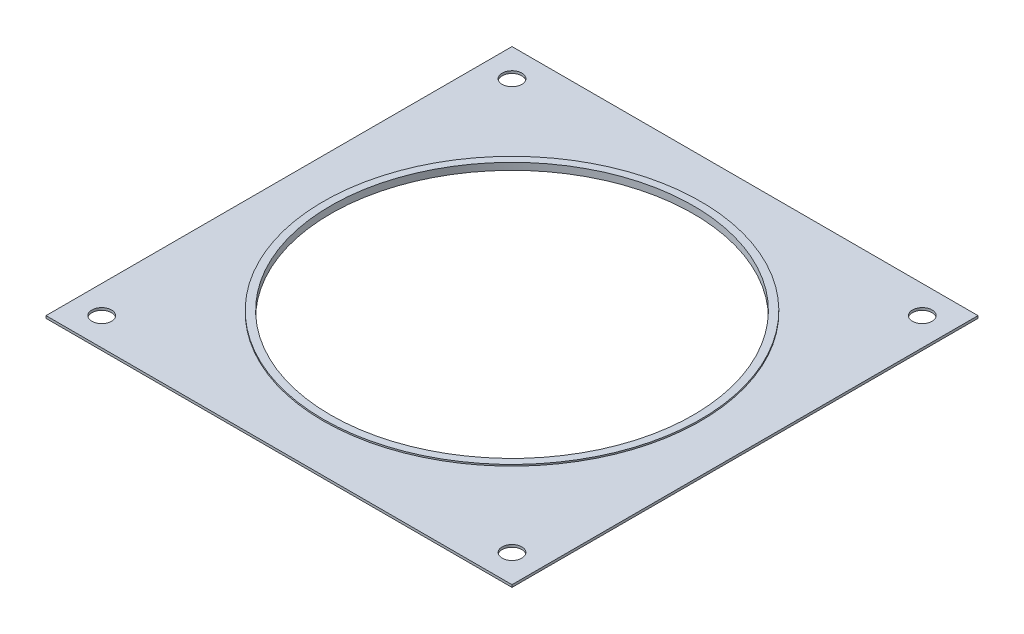
SolidWorks part; units mm, degrees
material "AISI 1020"
ref_plane "Alzado" through (0, 0, 0) normal (0, 0, 1) x (1, 0, 0)
ref_plane "Planta" through (0, 0, 0) normal (0, 1, 0) x (1, 0, 0)
ref_plane "Vista lateral" through (0, 0, 0) normal (1, 0, 0) x (0, 0, -1)
sketch "Croquis1" plane through (0, 0, 0) normal (0, 1, 0) x (1, 0, 0)
  line L1 (-77.1, -77.1) -> (77.1, -77.1)
  line L2 (-77.1, -77.1) -> (-77.1, 77.1)
  line L3 (-77.1, 77.1) -> (77.1, 77.1)
  line L4 (77.1, -77.1) -> (77.1, 77.1)
  line L5 (-77.1, -77.1) -> (77.1, 77.1) construction
  line L6 (-77.1, 77.1) -> (77.1, -77.1) construction
  point P0 (0, 0)
  dimension "D1" = 154.2
  dimension "D2" = 154.2
extrude "Saliente-Extruir1" add sketch "Croquis1" along normal blind 0.8
sketch "Croquis2" plane through (0, 0.8, 0) normal (0, 1, 0) x (1, 0, 0)
  circle A0 centre (0, 0) radius 60
  dimension "D1" = 120
extrude "Cortar-Extruir1" cut sketch "Croquis2" against normal through all
sketch "Croquis3" plane through (0, 0.8, 0) normal (0, 1, 0) x (1, 0, 0)
  circle A0 centre (0, 0) radius 60
  circle A1 centre (0, 0) radius 60.9958
extrude "Saliente-Extruir2" add sketch "Croquis3" along normal blind 1
sketch "Croquis4" plane through (0, 1.8, 0) normal (0, 1, 0) x (1, 0, 0)
  circle A0 centre (0, 0) radius 60
  circle A1 centre (0, 0) radius 62.434
extrude "Saliente-Extruir3" add sketch "Croquis4" along normal blind 0.5
sketch "Croquis5" plane through (0, 0.8, 0) normal (0, 1, 0) x (1, 0, 0)
  line L0 (-77.1, 77.1) -> (77.1, -77.1) construction
  line L1 (-77.1, 77.1) -> (-42.4264, 42.4264) construction
  line L2 (0, -90.57) -> (0, 113.2656) construction
  line L3 (-91.2965, 0) -> (110.057, 0) construction
  circle A0 centre (0, 0) radius 60
  circle A1 centre (-67.8823, 67.8823) radius 3.25
  circle A2 centre (-67.8823, -67.8823) radius 3.25
  circle A3 centre (67.8823, -67.8823) radius 3.25
  circle A4 centre (67.8823, 67.8823) radius 3.25
  dimension "D1" = 6.5
  dimension "D2" = 36
extrude "Cortar-Extruir2" cut sketch "Croquis5" against normal through all contours A1 | A4 | A2 | A3
